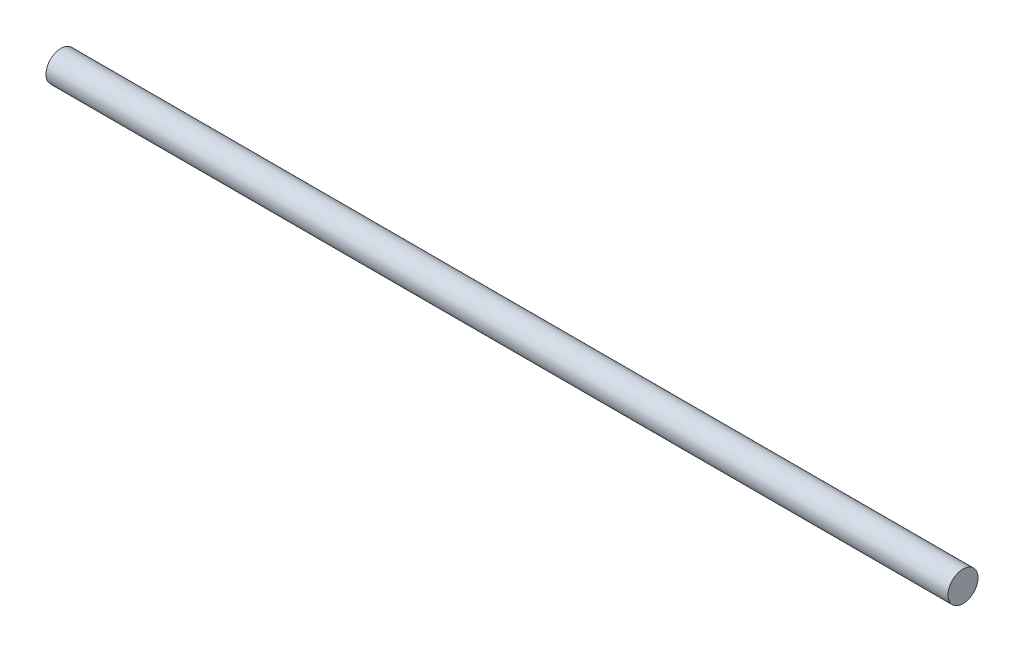
SolidWorks part; units mm, degrees
material "3004-H34, Rod (SS)"
ref_plane "Front Plane" through (0, 0, 0) normal (1, 0, 0) x (0, 1, 0)
ref_plane "Top Plane" through (0, 0, 0) normal (0, 0, 1) x (0, 1, 0)
ref_plane "Right Plane" through (0, 0, 0) normal (0, 1, 0) x (-1, 0, 0)
sketch "Sketch1" plane through (0, 0, 0) normal (1, 0, 0) x (0, 1, 0)
  circle A0 centre (0, 0) radius 3.175
  dimension "D1" = 6.35
extrude "Boss-Extrude1" add sketch "Sketch1" along normal blind 190.7634
equation "\"def\" = 0.009"
equation "\"P\"= 500'pound force"
equation "\"E\"= 8.5 * 10 ^ 6'young's"
equation "\"D\" = .25'Diameter"
equation "\"Area\" = ( pi / 4 ) * \"D\" ^ 2"
equation "\"L\"= ( \"Area\" * \"E\" * \"def\" ) / \"P\""
equation "\"D1@Sketch1\"=\"D\""
equation "\"D1@Boss-Extrude1\"=\"L\""
